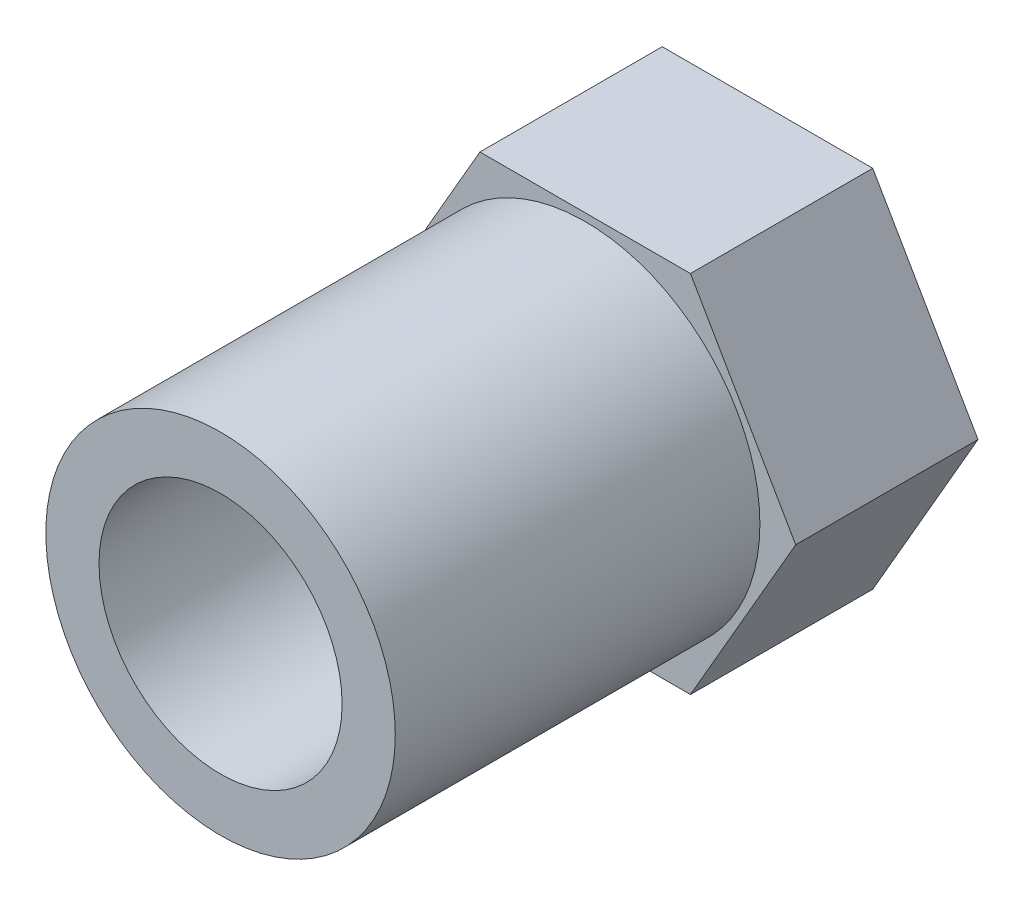
SolidWorks part; units mm, degrees
ref_plane "Front Plane" through (0, 0, 0) normal (0, 0, 1) x (1, 0, 0)
ref_plane "Top Plane" through (0, 0, 0) normal (0, 1, 0) x (1, 0, 0)
ref_plane "Right Plane" through (0, 0, 0) normal (1, 0, 0) x (0, 0, -1)
sketch "Sketch2" plane through (0, 0, 0) normal (0, 0, 1) x (1, 0, 0)
  circle A0 centre (0, 0) radius 5.75
  circle A1 centre (0, 0) radius 4
  dimension "D1" = 11.5
  dimension "D2" = 8
extrude "Boss-Extrude1" add sketch "Sketch2" along normal blind 12
sketch "Sketch3" plane through (0, 0, 0) normal (0, 0, 1) x (1, 0, 0)
  line L0 (-3.4641, 6) -> (3.4641, 6)
  line L1 (3.4641, 6) -> (6.9282, 0)
  line L2 (6.9282, 0) -> (3.4641, -6)
  line L3 (3.4641, -6) -> (-3.4641, -6)
  line L4 (-3.4641, -6) -> (-6.9282, 0)
  line L5 (-6.9282, 0) -> (-3.4641, 6)
  line L6 (-6.9282, 0) -> (6.9282, 0) construction
  line L7 (-3.4641, 6) -> (3.4641, -6) construction
  line L8 (3.4641, 6) -> (-3.4641, -6) construction
  circle A0 centre (0, 0) radius 6.9282
  dimension "D1" = 12
extrude "Boss-Extrude2" add sketch "Sketch3" against normal blind 6 contours L5 L4 L3 L2 L1 L0
hole_wizard "M4x0.7 Tapped Hole1" positions "3DSketch2" profile "Sketch4" tap size "M4x0.7" standard "ANSI Metric" end condition through all
sketch3d "3DSketch2"
  line L0 (3.4641, 6, -6) -> (-3.4641, -6, -6) construction
  line L2 (-3.4641, 6, -6) -> (3.4641, -6, -6) construction
  point P0 (0, 0, -6)
sketch "Sketch4" plane through (0, 0, -6) normal (1, 0, 0) x (0, 1, 0)
  line L0 (0, 0) -> (0, 18)
  line L1 (0, 18) -> (1.65, 18)
  line L2 (1.65, 18) -> (1.65, 0)
  line L5 (1.65, 0) -> (0, 0)
  line L11 (0, -6.35) -> (0, 107.95) construction
  dimension "Thru Tap Drill Dia." = 3.3
  dimension "Thru Tap Drill Depth" = 18
